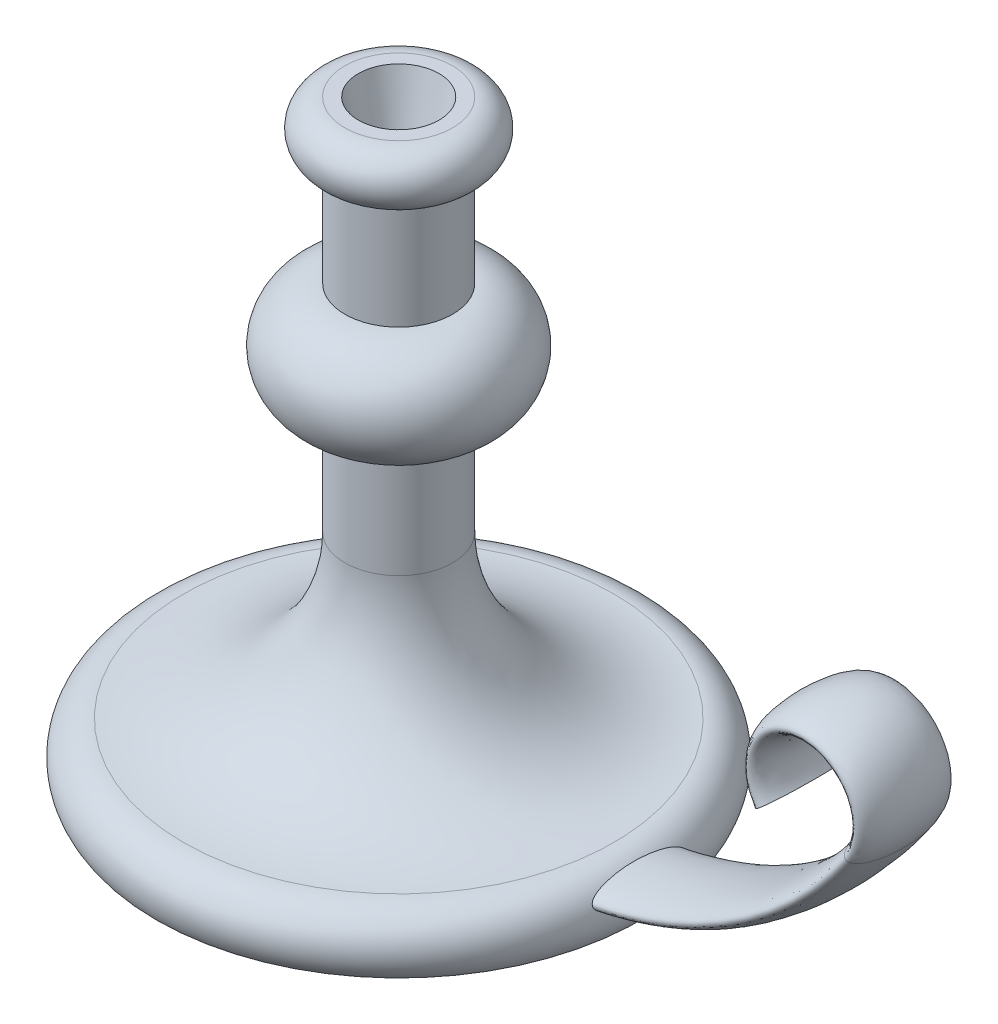
SolidWorks part; units mm, degrees
ref_plane "Спереди" through (0, 0, 0) normal (0, 0, 1) x (1, 0, 0)
ref_plane "Сверху" through (0, 0, 0) normal (0, 1, 0) x (1, 0, 0)
ref_plane "Справа" through (0, 0, 0) normal (1, 0, 0) x (0, 0, -1)
sketch "Эскиз1" plane through (0, 0, 0) normal (0, 0, 1) x (1, 0, 0)
  line L0 (0, 0) -> (0, 220)
  line L1 (0, 220) -> (20, 220)
  line L2 (0, 0) -> (90, 0)
  line L3 (20, 200) -> (20, 160)
  line L4 (20, 120) -> (20, 80)
  arc A0 (20, 220) -> (20, 200) centre (20, 210) cw
  arc A1 (20, 120) -> (20, 160) centre (20, 140) ccw
  arc A2 (20, 80) -> (80, 20) centre (80, 80) ccw
  arc A3 (80, 20) -> (90, 0) centre (80, 7.5) cw
  dimension "D4" = 10
  dimension "D5" = 20
  dimension "D8" = 60
  dimension "D9" = 12.5
  dimension "D1" = 220
  dimension "D2" = 20
  dimension "D3" = 90
  dimension "D6" = 40
  dimension "D7" = 80
revolve "Повернуть1" add sketch "Эскиз1" angle 360 about L0
sketch "Эскиз2" plane through (0, 0, 0) normal (0, 0, 1) x (1, 0, 0)
  line L0 (0, 10) -> (60, 10)
  line L1 (0, 227.4356) -> (0, 175.1288) construction
  line L2 (0, 200) -> (0, 160) construction
  arc A0 (60, 10) -> (183.5921, 75) centre (60, 160) ccw
  arc A1 (183.5921, 75) -> (150.6342, 75) centre (167.1131, 86.3333) ccw
  dimension "D2" = 150
  dimension "D4" = 10
  dimension "D1" = 60
  dimension "D3" = 65
sketch "Эскиз3" plane through (0, 0, 0) normal (1, 0, 0) x (0, 0, -1)
  ellipse E0 centre (0, 10) end of major axis (-17.5, 10) minor radius 5
  dimension "D1" = 35
  dimension "D2" = 10
sweep "По траектории1" add profiles "Эскиз3" path "Эскиз2"
sketch "Эскиз5" plane through (0, 220, 0) normal (0, 1, 0) x (1, 0, 0)
  circle A0 centre (0, 0) radius 15
extrude "Вырез-Вытянуть1" cut sketch "Эскиз5" against normal blind 25 draft 15
